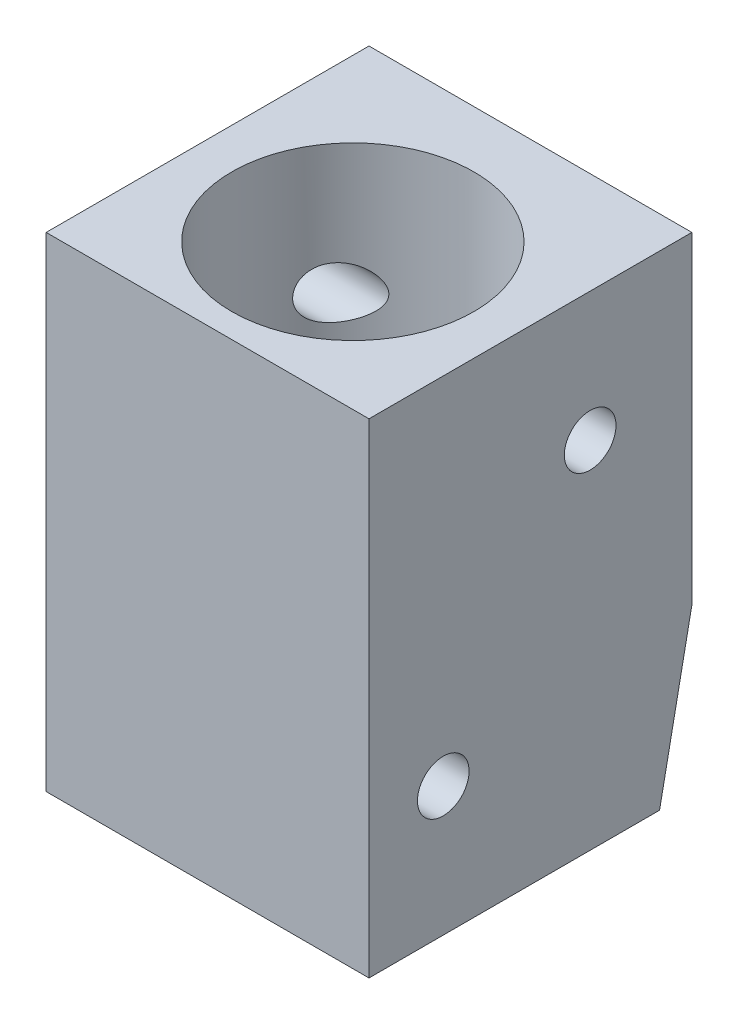
SolidWorks part; units mm, degrees
ref_plane "Front Plane" through (0, 0, 0) normal (0, 0, 1) x (1, 0, 0)
ref_plane "Top Plane" through (0, 0, 0) normal (0, 1, 0) x (1, 0, 0)
ref_plane "Right Plane" through (0, 0, 0) normal (1, 0, 0) x (0, 0, -1)
sketch "Sketch1" plane through (0, 0, 0) normal (0, 1, 0) x (1, 0, 0)
  line L0 (0, 0) -> (10, 0)
  line L1 (10, 0) -> (10, 10)
  line L2 (10, 10) -> (0, 10)
  line L3 (0, 10) -> (0, 0)
extrude "Boss-Extrude1" add sketch "Sketch1" along normal blind 15
hole_wizard "#97 (0.0059) Diameter Hole1" positions "Sketch3" profile "Sketch2" hole size "#97" standard "ANSI Inch" end condition through all
sketch "Sketch3" plane through (0, 15, 0) normal (0, 1, 0) x (1, 0, 0)
  line L0 (0, 0) -> (10, 0) construction
  line L1 (0, 10) -> (0, 0) construction
  point P0 (5, 4.5)
  dimension "D1" = 4.5
  dimension "D2" = 5
sketch "Sketch2" plane through (5, 15, -4.5) normal (1, 0, 0) x (0, 0, 1)
  line L0 (0, 0) -> (0, 15)
  line L1 (0, 15) -> (3.75, 15)
  line L2 (3.75, 15) -> (3.75, 0)
  line L5 (3.75, 0) -> (0, 0)
  line L11 (0, -6.35) -> (0, 107.95) construction
  dimension "Thru Hole Dia." = 7.5
  dimension "Thru Hole Depth" = 15
sketch "Sketch4" plane through (10, 0, 0) normal (1, 0, 0) x (0, 0, -1)
  line L0 (10, 0) -> (9, 0)
  line L1 (0, 0) -> (10, 0) construction
  line L2 (9, 0) -> (10, 5)
  line L3 (10, 0) -> (10, 5)
  line L6 (10, 15) -> (10, 0) construction
extrude "Cut-Extrude1" cut sketch "Sketch4" against normal blind 15
hole_wizard "#0-80 Tapped Hole1" positions "Sketch6" profile "Sketch5" tap size "#0-80" standard "ANSI Inch"
sketch "Sketch6" plane through (0, -1.7308, -8.6538) normal (0, -0.1961, -0.9806) x (-1, 0, 0)
  line L0 (0, 6.8641) -> (-10, 6.8641) construction
  line L1 (-10, 6.8641) -> (-10, 1.765) construction
  point P0 (-5, 5.6641)
  point P2 (-5, 2.8641)
  dimension "D1" = 1.2
  dimension "D2" = 4
  dimension "D3" = 5
  dimension "D4" = 5
sketch "Sketch5" plane through (5, 3.8233, -9.7647) normal (1, 0, 0) x (0, 0.9806, -0.1961)
  line L0 (0, 0) -> (0, 5.3079)
  line L1 (0, 5.3079) -> (0.5956, 4.95)
  line L2 (0.5956, 4.95) -> (0.5956, 0)
  line L5 (0.5956, 0) -> (0, 0)
  line L10 (0, 5.3079) -> (-0.5956, 4.95) construction
  line L11 (0, -6.35) -> (0, 107.95) construction
  dimension "Tap Drill Dia." = 1.1913
  dimension "Tap Drill Depth" = 4.95
  dimension "Drill Angle" = 118
hole_wizard "M2x0.4 Tapped Hole1" positions "Sketch8" profile "Sketch7" tap size "M2x0.4" standard "ANSI Metric"
sketch "Sketch8" plane through (10, 0, 0) normal (1, 0, 0) x (0, 0, -1)
  line L0 (0, 15) -> (10, 15) construction
  line L1 (0, 15) -> (0, 0) construction
  line L2 (0, 0) -> (9, 0) construction
  line L3 (10, 15) -> (10, 5) construction
  point P2 (2.3, 4)
  point P13 (6.85, 11)
  dimension "D3" = 4
  dimension "2.3mm" = 2.3
  dimension "D4" = 4
  dimension "D5" = 3.15
sketch "Sketch7" plane through (10, 4, -2.3) normal (0, 1, 0) x (0, 0, -1)
  line L0 (0, 0) -> (0, 5.6807)
  line L1 (0, 5.6807) -> (0.8, 5.2)
  line L2 (0.8, 5.2) -> (0.8, 0)
  line L5 (0.8, 0) -> (0, 0)
  line L10 (0, 5.6807) -> (-0.8, 5.2) construction
  line L11 (0, -6.35) -> (0, 107.95) construction
  dimension "Tap Drill Dia." = 1.6
  dimension "Tap Drill Depth" = 5.2
  dimension "Drill Angle" = 118
ref_plane "Plane1" through (5, 0, 0) normal (1, 0, 0) x (0, 0, -1)
mirror "Mirror1" about plane through (5, 0, 0) normal (1, 0, 0) of "M2x0.4 Tapped Hole1"
